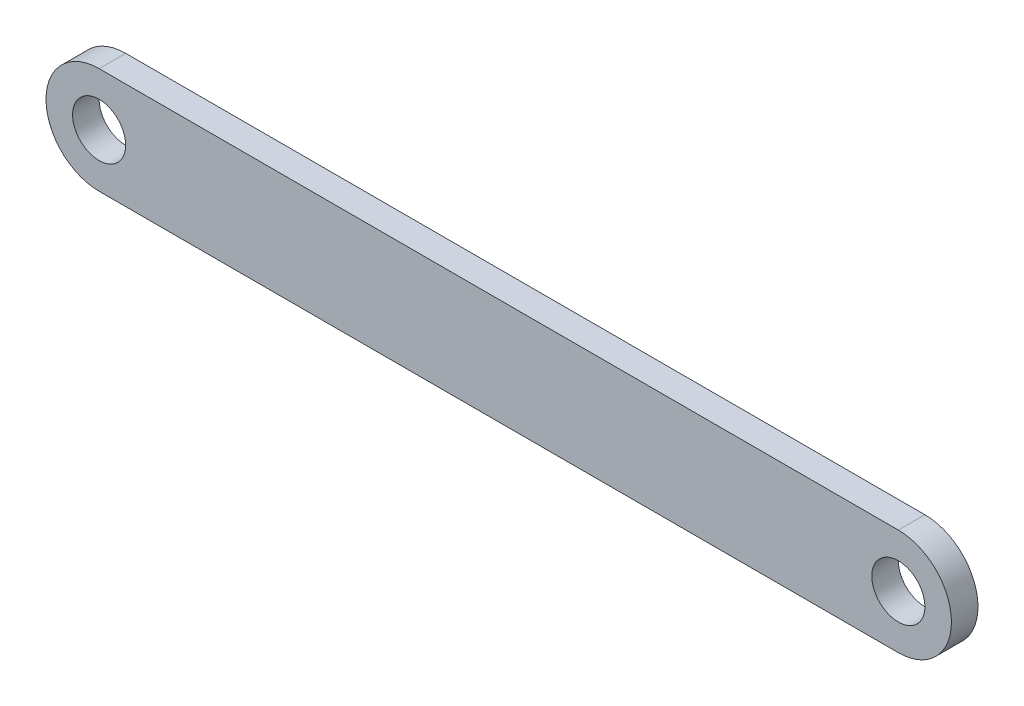
SolidWorks part; units mm, degrees
ref_plane "Front Plane" through (0, 0, 0) normal (0, 0, 1) x (1, 0, 0)
ref_plane "Top Plane" through (0, 0, 0) normal (0, 1, 0) x (1, 0, 0)
ref_plane "Right Plane" through (0, 0, 0) normal (1, 0, 0) x (0, 0, -1)
sketch "Sketch1" plane through (0, 0, 0) normal (0, 0, 1) x (1, 0, 0)
  line L0 (191.135, 0) -> (-191.135, 0)
  line L1 (-191.135, 0) -> (191.135, 0) construction
  line L2 (-191.135, 25.4) -> (191.135, 25.4)
  line L3 (-191.135, -25.4) -> (191.135, -25.4)
  line L4 (0, -55) -> (0, 55) construction
  arc A0 (-191.135, 25.4) -> (-191.135, -25.4) centre (-191.135, 0) ccw
  arc A1 (191.135, -25.4) -> (191.135, 25.4) centre (191.135, 0) ccw
  circle A2 centre (-191.135, 0) radius 12.7
  circle A3 centre (191.135, 0) radius 12.7
  point P0 (0, 0)
  point P4 (0, 0)
  dimension "D3" = 25.4
  dimension "D1" = 382.27
  dimension "D2" = 50.8
extrude "Boss-Extrude1" add sketch "Sketch1" along normal mid plane 12.7
